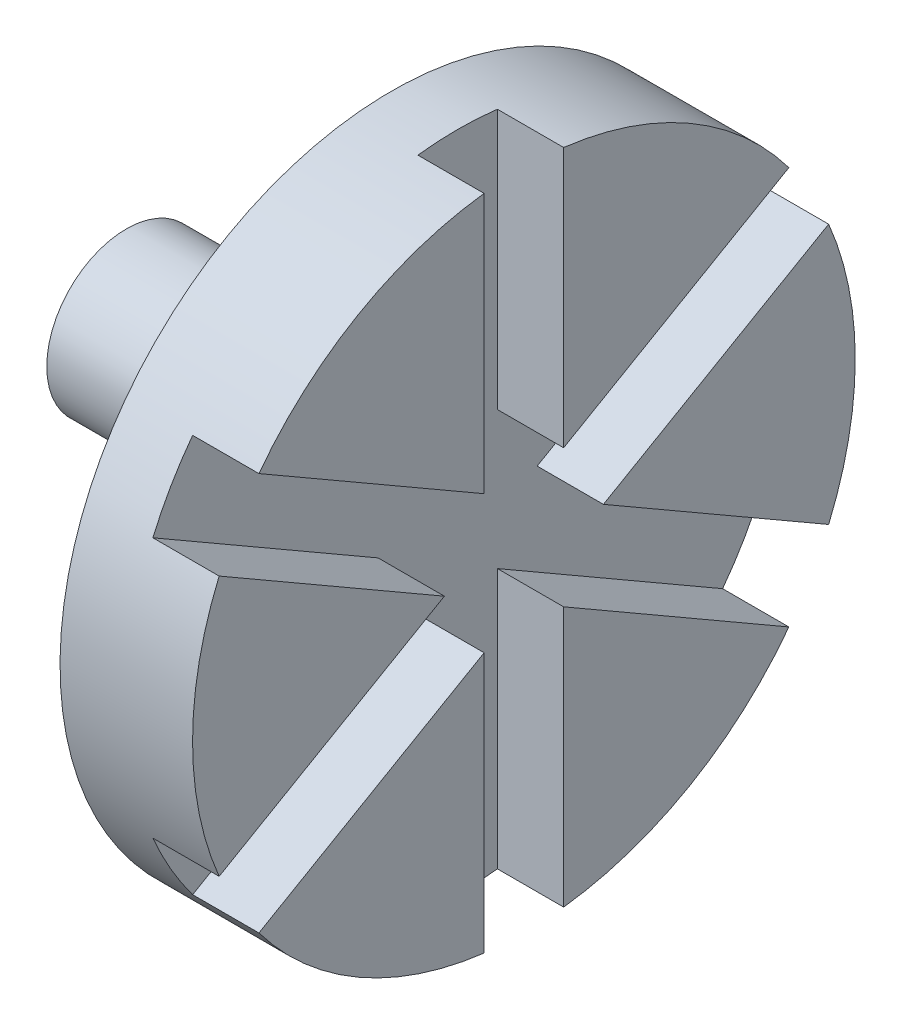
SolidWorks part; units mm, degrees
ref_plane "Front Plane" through (0, 0, 0) normal (0, 0, 1) x (1, 0, 0)
ref_plane "Top Plane" through (0, 0, 0) normal (0, 1, 0) x (1, 0, 0)
ref_plane "Right Plane" through (0, 0, 0) normal (1, 0, 0) x (0, 0, -1)
sketch "Sketch1" plane through (0, 0, 0) normal (1, 0, 0) x (0, 0, -1)
  circle A0 centre (0, 0) radius 50
  dimension "D1" = 100
extrude "Boss-Extrude1" add sketch "Sketch1" along normal blind 10
sketch "Sketch7" plane through (10, 0, 0) normal (1, 0, 0) x (0, 0, -1)
  line L0 (12, 0) -> (45.9884, -19.6232)
  line L1 (12, 0) -> (45.9884, 19.6232)
  line L2 (6, -10.3923) -> (6, -49.6387)
  line L3 (6, 10.3923) -> (39.9884, 30.0155)
  line L4 (6, 10.3923) -> (6, 49.6387)
  line L5 (6, -10.3923) -> (39.9884, -30.0155)
  line L6 (-6, -10.3923) -> (-39.9884, -30.0155)
  line L7 (-6, -10.3923) -> (-6, -49.6387)
  line L8 (-12, 0) -> (-45.9884, 19.6232)
  line L9 (-12, 0) -> (-45.9884, -19.6232)
  line L10 (-6, 10.3923) -> (-6, 49.6387)
  line L11 (-6, 10.3923) -> (-39.9884, 30.0155)
  line L12 (0, 0) -> (6, 10.3923) construction
  line L13 (0, 0) -> (12, 0) construction
  arc A0 (6, 49.6387) -> (39.9884, 30.0155) centre (0, 0) cw
  circle A2 centre (0, 0) radius 50 construction
  arc A3 (45.9884, 19.6232) -> (45.9884, -19.6232) centre (0, 0) cw
  arc A4 (39.9884, -30.0155) -> (6, -49.6387) centre (0, 0) cw
  arc A5 (-6, -49.6387) -> (-39.9884, -30.0155) centre (0, 0) cw
  arc A6 (-45.9884, -19.6232) -> (-45.9884, 19.6232) centre (0, 0) cw
  arc A7 (-39.9884, 30.0155) -> (-6, 49.6387) centre (0, 0) cw
  point P2 (12, 0)
  point P4 (6, 10.3923)
  point P9 (6, -10.3923)
  point P19 (-6, -10.3923)
  point P23 (-12, 0)
  point P27 (-6, 10.3923)
  dimension "D1" = 6
  dimension "D2" = 60
extrude "Boss-Extrude2" add sketch "Sketch7" along normal blind 10
sketch "Sketch9" plane through (0, 0, 0) normal (-1, 0, 0) x (0, 0, 1)
  circle A0 centre (0, 0) radius 12
  dimension "D1" = 24
extrude "Boss-Extrude3" add sketch "Sketch9" along normal blind 40
